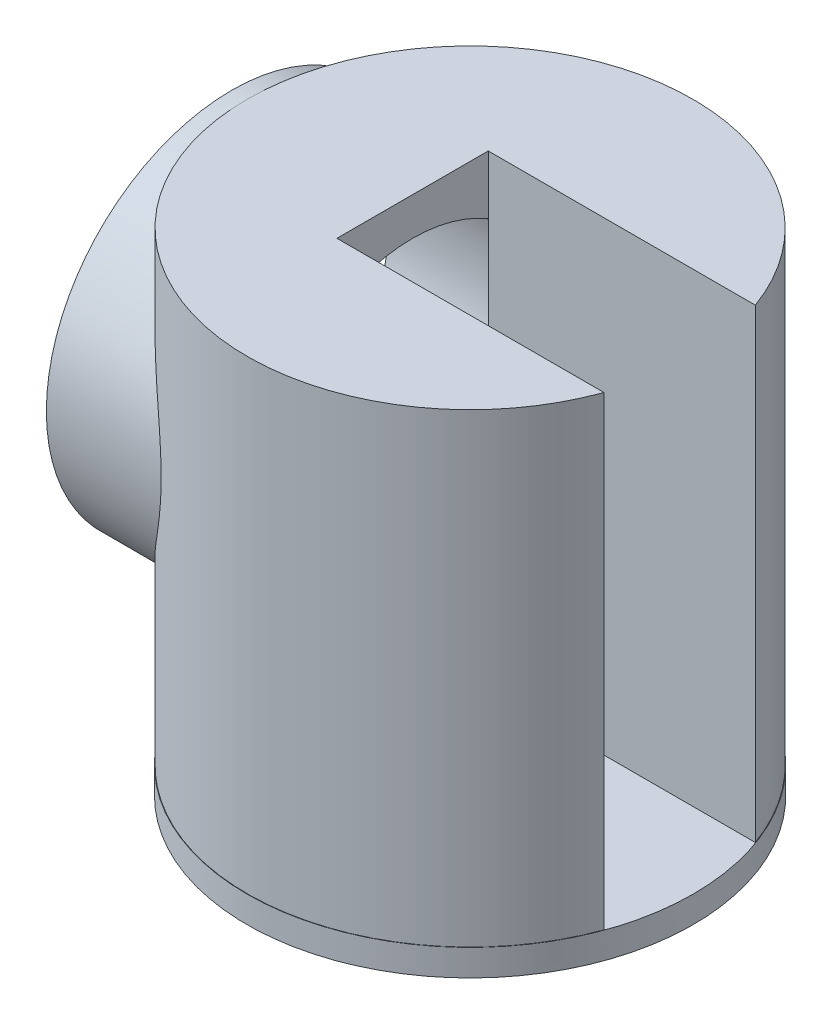
SolidWorks part; units mm, degrees
ref_plane "Спереди" through (0, 0, 0) normal (0, 0, 1) x (1, 0, 0)
ref_plane "Сверху" through (0, 0, 0) normal (0, 1, 0) x (1, 0, 0)
ref_plane "Справа" through (0, 0, 0) normal (1, 0, 0) x (0, 0, -1)
sketch "Эскиз1" plane through (0, 0, 0) normal (0, 1, 0) x (1, 0, 0)
  circle A0 centre (0, 0) radius 29.5
  dimension "D1" = 59
extrude "Бобышка-Вытянуть1" add sketch "Эскиз1" along normal blind 4
sketch "Эскиз2" plane through (0, 4, 0) normal (0, 1, 0) x (1, 0, 0)
  circle A0 centre (7, 0) radius 1.5
  dimension "D2" = 3
  dimension "D1" = 7
extrude "Вырез-Вытянуть1" cut sketch "Эскиз2" against normal through all
pattern_circular "Круговой массив1" count 4 over 360 about axis through (0, 0, 0) along (0, 1, 0) of "Вырез-Вытянуть1"
sketch "Эскиз3" plane through (0, 4, 0) normal (0, 1, 0) x (1, 0, 0)
  circle A0 centre (0, 0) radius 29.4449
extrude "Бобышка-Вытянуть2" add sketch "Эскиз3" along normal blind 61.5
sketch "Эскиз4" plane through (0, 65.5, 0) normal (0, 1, 0) x (1, 0, 0)
  line L0 (0, 0) -> (41.3001, 0) construction
  line L2 (-7.6, 10) -> (31.9, 10)
  line L3 (-7.6, 10) -> (-7.6, -10)
  line L4 (-7.6, -10) -> (31.9, -10)
  line L5 (31.9, 10) -> (31.9, -10)
  dimension "D1" = 7.6
  dimension "D2" = 39.5
  dimension "D3" = 20
  dimension "D4" = 10
extrude "Вырез-Вытянуть2" cut sketch "Эскиз4" against normal blind 61.5
sketch "Эскиз7" plane through (0, 0, 0) normal (1, 0, 0) x (0, 0, -1)
  circle A0 centre (0, 41) radius 21
  circle A1 centre (0, 41) radius 24.5
  dimension "D2" = 42
  dimension "D3" = 49
  dimension "D1" = 41
extrude "Бобышка-Вытянуть3" add sketch "Эскиз7" against normal blind 21.5 from offset 10 offset against normal yes
sketch "Эскиз11" plane through (-31.5, 0, 0) normal (-1, 0, 0) x (0, 0, 1)
  circle A0 centre (0, 41) radius 21
  dimension "D2" = 42
  dimension "D1" = 41
extrude "Вырез-Вытянуть7" cut sketch "Эскиз11" against normal blind 17
sketch "Эскиз12" plane through (-31.5, 0, 0) normal (-1, 0, 0) x (0, 0, 1)
  circle A0 centre (0, 41) radius 19.5
  dimension "D2" = 39
  dimension "D1" = 41
extrude "Вырез-Вытянуть10" cut sketch "Эскиз12" against normal up to surface (23.9 mm away) up to face at (-7.6, 24.5, 0)
sketch "Эскиз13" plane through (0, 0, 0) normal (0, -1, 0) x (1, 0, 0)
  circle A0 centre (0, 0) radius 29.5
  circle A1 centre (0, 0) radius 19.5
  dimension "D1" = 59
  dimension "D2" = 39
extrude "Вырез-Вытянуть11" cut sketch "Эскиз13" against normal blind 0.5
